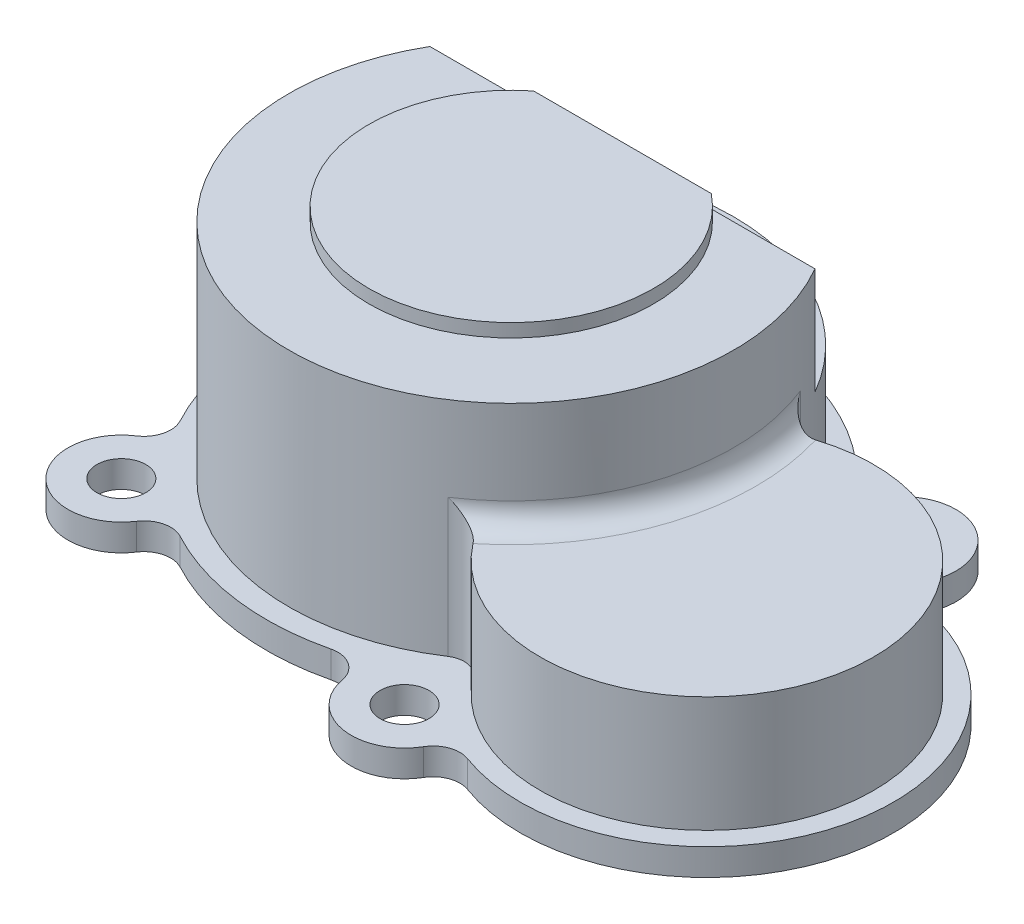
SolidWorks part; units mm, degrees
ref_plane "Front" through (0, 0, 0) normal (0, 0, 1) x (1, 0, 0)
ref_plane "Top" through (0, 0, 0) normal (0, 1, 0) x (1, 0, 0)
ref_plane "Right" through (0, 0, 0) normal (1, 0, 0) x (0, 0, -1)
sketch "Sketch1" plane through (0, 0, 0) normal (0, 1, 0) x (1, 0, 0)
  arc A0 (21.2118, -50.745) -> (43.9652, -56.9135) centre (32, -56) ccw
  arc A2 (62.5978, 21.9766) -> (44.0376, 32.9497) centre (56, 32) ccw
  arc A3 (44.0376, 32.9497) -> (-31.8805, 44.8178) centre (0, 0) ccw
  arc A4 (43.9652, -56.9135) -> (62.5978, 21.9766) centre (64, -20) ccw
  arc A5 (-31.8805, 44.8178) -> (-44.8178, 31.8805) centre (-43.8406, 43.8406) ccw
  arc A6 (-44.8178, 31.8805) -> (-44.8178, -31.8805) centre (0, 0) ccw
  arc A7 (-44.8178, -31.8805) -> (-31.8805, -44.8178) centre (-43.8406, -43.8406) ccw
  arc A8 (-31.8805, -44.8178) -> (21.2118, -50.745) centre (0, 0) ccw
extrude "Boss-Extrude1" add sketch "Sketch1" along normal blind 6 contours A4 A2 A3 A5 A6 A7 A8 A0
sketch "Sketch2" plane through (0, 6, 0) normal (0, 1, 0) x (1, 0, 0)
  circle A0 centre (56, 32) radius 5.5
  circle A1 centre (-43.8406, 43.8406) radius 5.5
  circle A2 centre (-43.8406, -43.8406) radius 5.5
  circle A3 centre (32, -56) radius 5.5
extrude "Cut-Extrude1" cut sketch "Sketch2" against normal blind 6
sketch "Sketch3" plane through (0, 6, 0) normal (0, 1, 0) x (1, 0, 0)
  line L0 (0, 0) -> (0, 59.0026) construction
  line L1 (0, 0) -> (0, -41.1369) construction
  line L2 (0, 0) -> (35.3117, 0) construction
  line L3 (0, 0) -> (-36.6479, 0) construction
  line L4 (64, 11.5529) -> (64, -83.8564) construction
  line L5 (28.2197, -20) -> (103.3395, -20) construction
  circle A0 centre (0, 0) radius 50
  dimension "D1" = 64
  dimension "D2" = 20
extrude "Boss-Extrude2" add sketch "Sketch3" along normal blind 50
sketch "Sketch4" plane through (0, 6, 0) normal (0, 1, 0) x (1, 0, 0)
  line L0 (0, 0) -> (0, 42.5643) construction
  line L1 (0, 0) -> (0, -43.3175) construction
  line L2 (0, 0) -> (47.892, 0) construction
  line L3 (64, 2.1395) -> (64, -71.4975) construction
  line L4 (54.4338, -20) -> (102.0714, -20) construction
  line L5 (31.5477, -38.791) -> (117.2265, -38.791) construction
  line L6 (31.5477, -38.791) -> (-1.2681, -38.791) construction
  line L7 (48.0217, 13.9255) -> (126.1389, 13.9255) construction
  line L8 (48.0217, 13.9255) -> (6.0239, 13.9255) construction
  circle A0 centre (64, -20) radius 37.5
  circle A1 centre (0, 0) radius 50 construction
  circle A2 centre (0, 0) radius 50 construction
  dimension "D1" = 64
  dimension "D2" = 20
extrude "Boss-Extrude3" add sketch "Sketch4" along normal blind 26 contours A0
sketch "Sketch5" plane through (0, 56, 0) normal (0, 1, 0) x (1, 0, 0)
  circle A0 centre (0, 0) radius 32
extrude "Boss-Extrude4" add sketch "Sketch5" along normal blind 3
fillet "Fillet2" radius 6 1 edges at (44.0376, 3, -32.9497)
fillet "Fillet3" radius 6 7 edges at (-44.8178, 3, -31.8805) (-44.8178, 3, 31.8805) (-31.8805, 3, 44.8178) (21.2118, 3, 50.745) (43.9652, 3, 56.9135) (62.5978, 3, -21.9766) (-31.8805, 3, -44.8178)
fillet "Fillet4" radius 5 3 edges at (47.724, 32, 14.9137) (31.5477, 19, 38.791) (48.0217, 19, -13.9255)
sketch "Sketch6" plane through (0, 59, 0) normal (0, 1, 0) x (1, 0, 0)
  line L0 (0, 0) -> (0, 25) construction
  line L1 (0, 25) -> (43.3013, 25)
  line L2 (0, 25) -> (-43.3013, 25)
  circle A0 centre (0, 0) radius 50 construction
  arc A1 (-43.3013, 25) -> (43.3013, 25) centre (0, 0) cw
extrude "Cut-Extrude2" cut sketch "Sketch6" against normal blind 27
